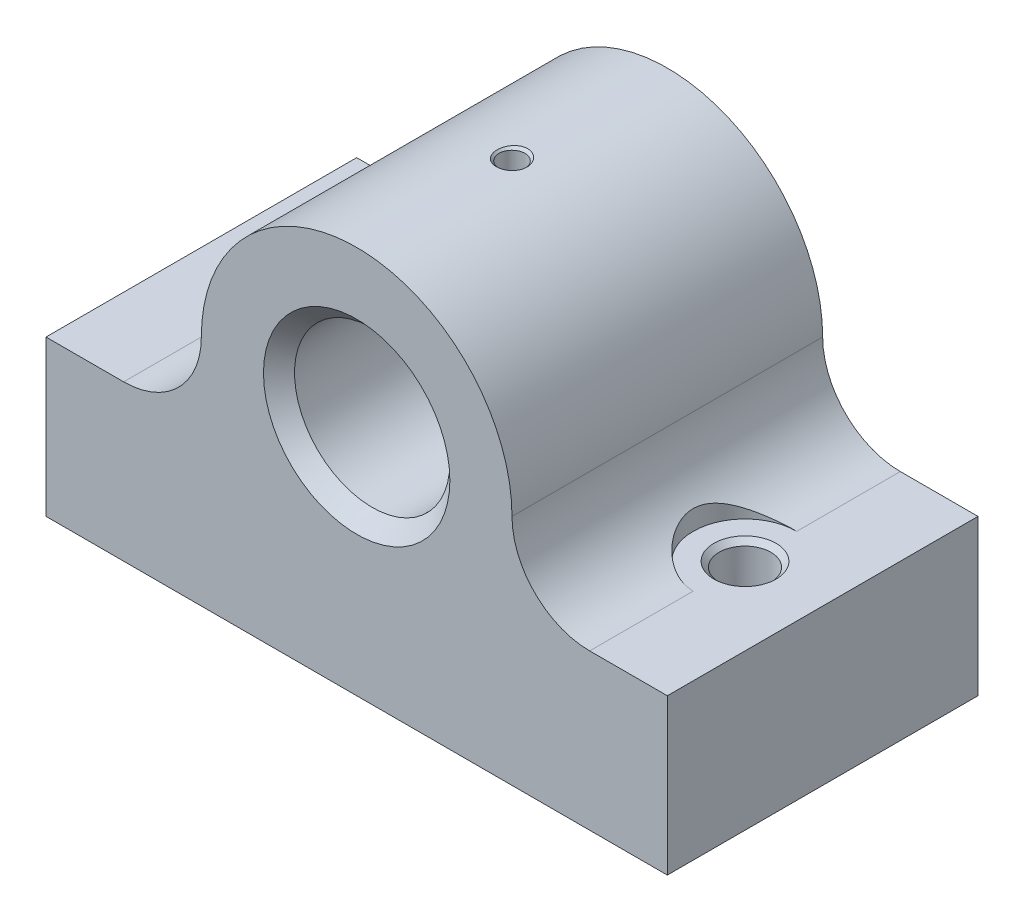
SolidWorks part; units mm, degrees
ref_plane "Front Plane" through (0, 0, 0) normal (0, 0, 1) x (1, 0, 0)
ref_plane "Top Plane" through (0, 0, 0) normal (0, 1, 0) x (1, 0, 0)
ref_plane "Right Plane" through (0, 0, 0) normal (1, 0, 0) x (0, 0, -1)
sketch "Sketch2" plane through (0, 0, 0) normal (0, 1, 0) x (1, 0, 0)
  line L1 (60, 30) -> (-60, 30)
  line L2 (60, 30) -> (60, -30)
  line L3 (60, -30) -> (-60, -30)
  line L4 (-60, 30) -> (-60, -30)
  line L5 (60, 30) -> (-60, -30) construction
  line L6 (60, -30) -> (-60, 30) construction
  point P0 (0, 0)
  dimension "D1" = 120
  dimension "D2" = 60
extrude "Boss-Extrude1" add sketch "Sketch2" along normal blind 30
sketch "Sketch4" plane through (0, 0, 30) normal (0, 0, 1) x (1, 0, 0)
  line L1 (-60, 30) -> (60, 30) construction
  circle A2 centre (0, 45) radius 30
  point P4 (0, 30)
  dimension "D1" = 15
  dimension "D2" = 60
extrude "Boss-Extrude2" add sketch "Sketch4" against normal blind 60 contours A2
sketch "Sketch6" plane through (0, 0, 30) normal (0, 0, 1) x (1, 0, 0)
  line L2 (-60, 30) -> (-25.9808, 30) construction
  circle A0 centre (0, 45) radius 15
  arc A1 (25.9808, 30) -> (-25.9808, 30) centre (0, 45) ccw construction
  dimension "D1" = 30
  dimension "D2" = 15
  dimension "D3" = 15
extrude "Cut-Extrude1" cut sketch "Sketch6" against normal through all
chamfer "Chamfer1" distance 3 angle 45 2 edges at (15, 45, -30) (15, 45, 30)
fillet "Fillet2" radius 15 2 edges at (25.9808, 30, 0) (-25.9808, 30, 0)
sketch "Sketch8" plane through (0, 30, 0) normal (0, 1, 0) x (1, 0, 0)
  line L0 (-45, -30) -> (-45, 30) construction
  line L1 (45, 30) -> (45, -30) construction
  circle A0 centre (-45, 0) radius 10
  circle A1 centre (45, 0) radius 10
  dimension "D1" = 20
  dimension "D2" = 20
extrude "Cut-Extrude3" cut sketch "Sketch8" along normal blind 38
sketch "Sketch9" plane through (0, 30, 0) normal (0, 1, 0) x (1, 0, 0)
  circle A0 centre (-45, 0) radius 5
  circle A1 centre (45, 0) radius 5
  dimension "D1" = 10
extrude "Cut-Extrude4" cut sketch "Sketch9" against normal through all
chamfer "Chamfer2" distance 1 angle 45 2 edges at (45, 30, 5) (-45, 30, 5)
ref_plane "Plane1" through (0, 75, 0) normal (0, 1, 0) x (1, 0, 0)
hole_wizard "M6 Tapped Hole2" positions "Sketch17" profile "Sketch18" tap size "M6" standard "ISO"
sketch "Sketch17" plane through (0, 75, 0) normal (0, 1, 0) x (1, 0, 0)
  point P3 (0, 0)
cosmetic thread "Hole Thread2" parameters "D2"=6
sketch "Sketch18" plane through (0, 75, 0) normal (1, 0, 0) x (0, 0, 1)
  line L0 (0, 0) -> (0, 31.5012)
  line L1 (0, 31.5012) -> (2.5, 29.999)
  line L2 (2.5, 29.999) -> (2.5, 0.525)
  line L3 (2.5, 0.525) -> (3.025, 0)
  line L5 (3.025, 0) -> (0, 0)
  line L6 (-2.5, 0.525) -> (-3.025, 0) construction
  line L10 (0, 31.5012) -> (-2.5, 29.999) construction
  line L11 (0, -6.35) -> (0, 107.95) construction
  dimension "Tap Drill Dia." = 5
  dimension "Tap Drill Depth" = 29.999
  dimension "Near C'Sink Dia." = 6.05
  dimension "Near C'Sink Angle" = 90
  dimension "Drill Angle" = 118
